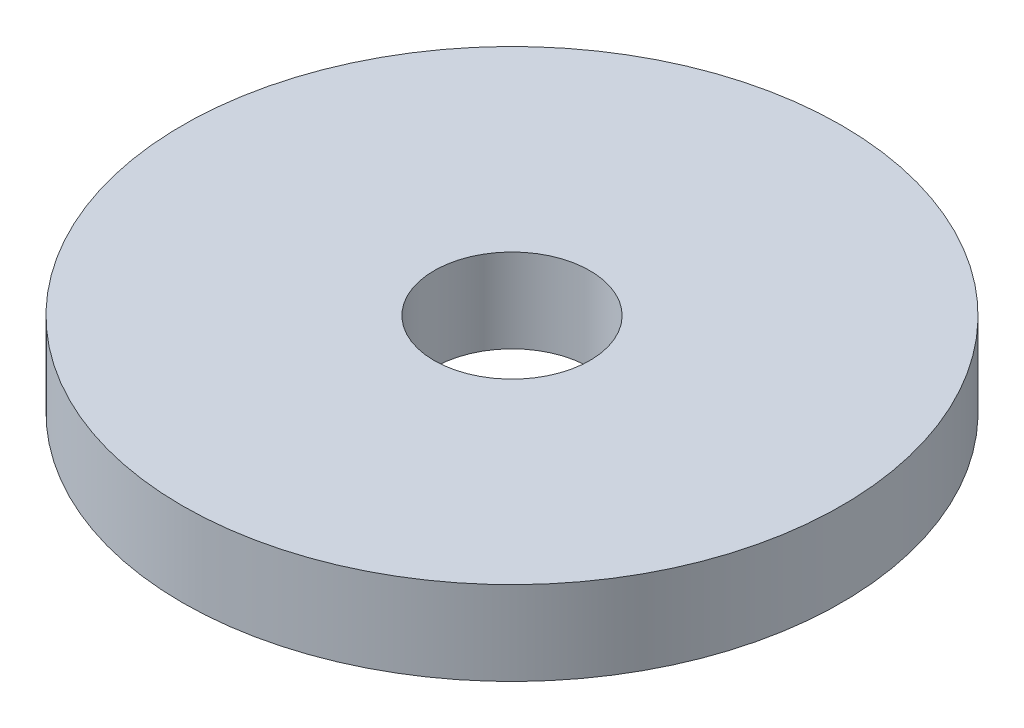
SolidWorks part; units mm, degrees
ref_plane "정면" through (0, 0, 0) normal (0, 0, 1) x (1, 0, 0)
ref_plane "윗면" through (0, 0, 0) normal (0, 1, 0) x (1, 0, 0)
ref_plane "우측면" through (0, 0, 0) normal (1, 0, 0) x (0, 0, -1)
sketch "스케치1" plane through (0, 0, 0) normal (0, 1, 0) x (1, 0, 0)
  circle A0 centre (0, 0) radius 5.5
  dimension "D1" = 11
extrude "보스-돌출1" add sketch "스케치1" along normal blind 1.4
sketch "스케치2" plane through (0, 1.4, 0) normal (0, 1, 0) x (1, 0, 0)
  point P0 (0, 0)
hole_wizard "M2 여유 구멍1" positions "스케치3" profile "스케치4" hole size "M2" standard "ISO"
sketch "스케치3" plane through (0, 1.4, 0) normal (0, 1, 0) x (1, 0, 0)
  point P0 (0, 0)
sketch "스케치4" plane through (0, 1.4, 0) normal (1, 0, 0) x (0, 0, 1)
  line L0 (0, 0) -> (0, 4.7811)
  line L1 (0, 4.7811) -> (1.3, 4)
  line L2 (1.3, 4) -> (1.3, 0)
  line L5 (1.3, 0) -> (0, 0)
  line L10 (0, 4.7811) -> (-1.3, 4) construction
  line L11 (0, -6.35) -> (0, 107.95) construction
  dimension "구멍 지름" = 2.6
  dimension "구멍 깊이" = 4
  dimension "드릴 각도" = 118
